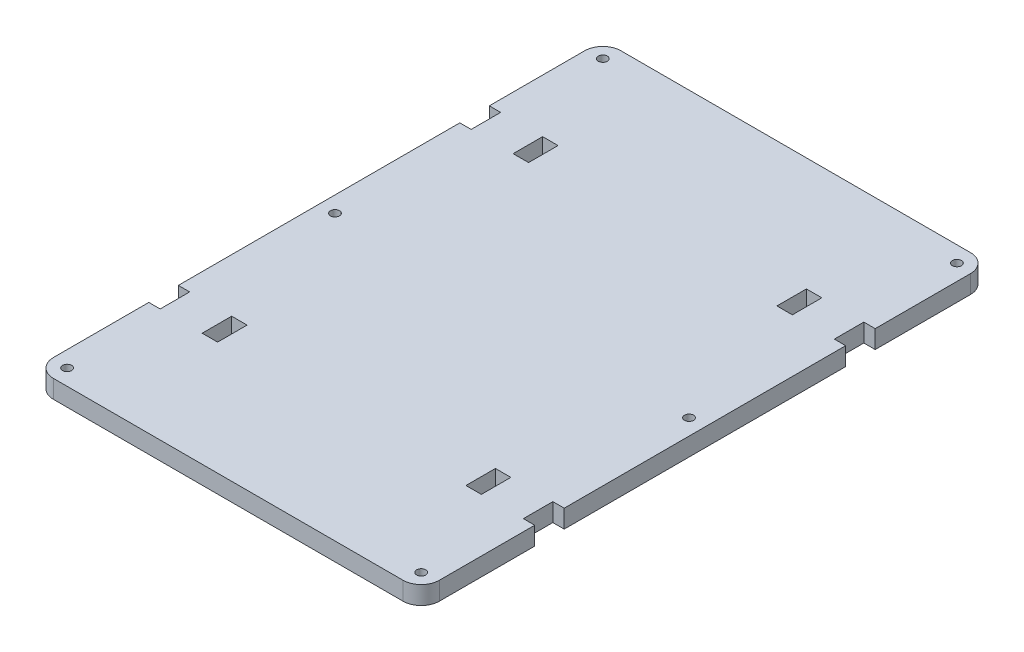
SolidWorks part; units mm, degrees
ref_plane "Front Plane" through (0, 0, 0) normal (0, 0, 1) x (1, 0, 0)
ref_plane "Top Plane" through (0, 0, 0) normal (0, 1, 0) x (1, 0, 0)
ref_plane "Right Plane" through (0, 0, 0) normal (1, 0, 0) x (0, 0, -1)
sketch "Sketch1" plane through (0, 0, 0) normal (0, 1, 0) x (1, 0, 0)
  line L1 (-85, 125) -> (85, 125)
  line L2 (-85, 125) -> (-85, -125)
  line L3 (-85, -125) -> (85, -125)
  line L4 (85, 125) -> (85, -125)
  line L5 (-85, 125) -> (85, -125) construction
  line L6 (-85, -125) -> (85, 125) construction
  point P0 (0, 0)
  dimension "D1" = 250
  dimension "D2" = 170
extrude "Boss-Extrude1" add sketch "Sketch1" along normal blind 8
sketch "Sketch2" plane through (0, 8, 0) normal (0, 1, 0) x (1, 0, 0)
  line L0 (85, 125) -> (-85, 125) construction
  line L1 (80, 75) -> (85, 75)
  line L2 (80, 75) -> (80, 62)
  line L3 (80, 62) -> (85, 62)
  line L4 (85, 75) -> (85, 62)
  line L5 (80, 75) -> (85, 62) construction
  line L6 (80, 62) -> (85, 75) construction
  line L7 (85, -125) -> (85, 125) construction
  line L8 (105.0231, 0) -> (-105.0231, 0) construction
  line L9 (0, 71.0915) -> (0, -71.0915) construction
  line L10 (-80, 62) -> (-85, 62)
  line L11 (-80, 75) -> (-80, 62)
  line L12 (-80, 75) -> (-85, 75)
  line L13 (-85, 75) -> (-85, 62)
  line L14 (80, -62) -> (85, -62)
  line L15 (85, -75) -> (85, -62)
  line L16 (80, -75) -> (80, -62)
  line L17 (80, -75) -> (85, -75)
  line L18 (-80, -62) -> (-85, -62)
  line L19 (-80, -75) -> (-85, -75)
  line L20 (-85, -75) -> (-85, -62)
  line L21 (-80, -75) -> (-80, -62)
  point P4 (82.5, 68.5)
  point P13 (0, 0)
  point P17 (0, 0)
  dimension "D1" = 50
  dimension "D2" = 5
  dimension "D3" = 13
extrude "Cut-Extrude1" cut sketch "Sketch2" against normal blind 8
sketch "Sketch3" plane through (0, 8, 0) normal (0, 1, 0) x (1, 0, 0)
  line L0 (-80, 62) -> (-80, 75) construction
  line L1 (-61.5, 75) -> (-54.7, 75)
  line L2 (-61.5, 75) -> (-61.5, 62)
  line L3 (-61.5, 62) -> (-54.7, 62)
  line L4 (-54.7, 75) -> (-54.7, 62)
  line L5 (-61.5, 75) -> (-54.7, 62) construction
  line L6 (-61.5, 62) -> (-54.7, 75) construction
  line L7 (-80, 75) -> (-85, 75) construction
  line L8 (-60.1498, 0) -> (60.1498, 0) construction
  line L9 (0, -57.7777) -> (0, 57.7777) construction
  line L10 (61.5, 62) -> (54.7, 62)
  line L11 (54.7, 75) -> (54.7, 62)
  line L12 (61.5, 75) -> (61.5, 62)
  line L13 (61.5, 75) -> (54.7, 75)
  line L14 (61.5, -62) -> (54.7, -62)
  line L15 (61.5, -75) -> (61.5, -62)
  line L16 (54.7, -75) -> (54.7, -62)
  line L17 (61.5, -75) -> (54.7, -75)
  line L18 (-61.5, -62) -> (-54.7, -62)
  line L19 (-61.5, -75) -> (-61.5, -62)
  line L20 (-54.7, -75) -> (-54.7, -62)
  line L21 (-61.5, -75) -> (-54.7, -75)
  line L22 (85, 125) -> (-85, 125) construction
  line L23 (-85, 125) -> (-85, 75) construction
  line L24 (-85, 62) -> (-85, -62) construction
  circle A0 centre (-78, 118) radius 2
  circle A1 centre (78, 118) radius 2
  circle A2 centre (78, -118) radius 2
  circle A3 centre (-78, -118) radius 2
  circle A4 centre (-78, 0) radius 2
  circle A5 centre (78, 0) radius 2
  point P4 (-58.1, 68.5)
  point P13 (0, 0)
  point P17 (0, 0)
  dimension "D4" = 7
  dimension "D6" = 7
  dimension "D1" = 18.5
  dimension "D2" = 13
  dimension "D3" = 6.8
  dimension "D5" = 7
  dimension "D7" = 50
extrude "Cut-Extrude2" cut sketch "Sketch3" against normal blind 8
fillet "Fillet1" radius 8 4 edges at (85, 4, 125) (-85, 4, 125) (85, 4, -125) (-85, 4, -125)
